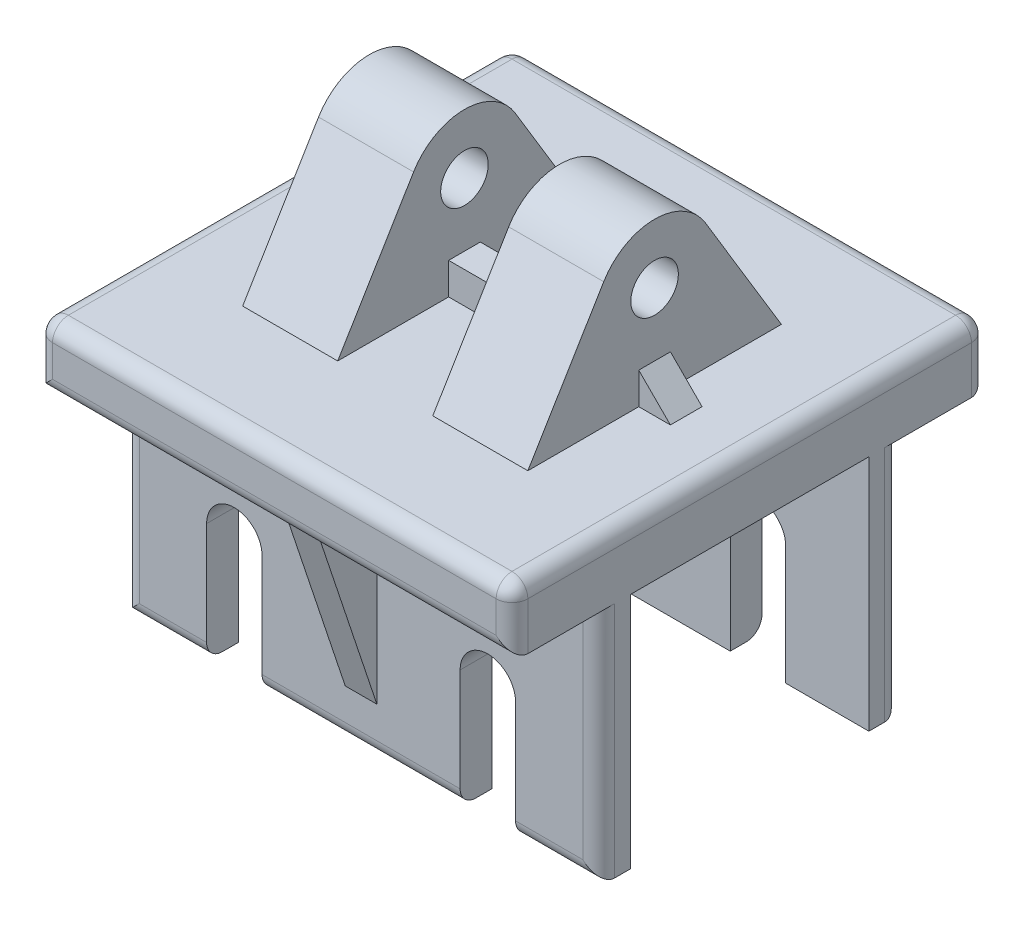
SolidWorks part; units mm, degrees
ref_plane "정면" through (0, 0, 0) normal (0, 0, 1) x (1, 0, 0)
ref_plane "윗면" through (0, 0, 0) normal (0, 1, 0) x (1, 0, 0)
ref_plane "우측면" through (0, 0, 0) normal (1, 0, 0) x (0, 0, -1)
sketch "스케치2" plane through (0, 0, 0) normal (1, 0, 0) x (0, 0, -1)
  line L0 (15.05, 0) -> (-15.05, 0)
  line L1 (-15.05, 0) -> (-15.05, -30)
  line L2 (-15.05, -30) -> (-19.05, -30)
  line L3 (-19.05, -30) -> (-19.05, 0)
  line L5 (19.05, 0) -> (19.05, -30)
  line L6 (19.05, -30) -> (15.05, -30)
  line L7 (15.05, -30) -> (15.05, 0)
  line L8 (-19.05, 0) -> (-30, 0)
  line L9 (-30, 0) -> (-30, 8)
  line L11 (19.05, 0) -> (30, 0)
  line L12 (30, 0) -> (30, 8)
  line L14 (-30, 8) -> (30, 8)
  point P5 (0, 8)
  point P16 (0, 0)
  dimension "D1" = 30.1
  dimension "D2" = 30
  dimension "D3" = 4
  dimension "D4" = 4
  dimension "D5" = 30
  dimension "D6" = 8
  dimension "D7" = 60
extrude "보스-돌출1" add sketch "스케치2" along normal mid plane 60
sketch "스케치3" plane through (0, 0, 0) normal (1, 0, 0) x (0, 0, -1)
  line L0 (-19.05, 0) -> (-27.05, 0)
  line L1 (-30, 0) -> (-19.05, 0) construction
  line L2 (-27.05, 0) -> (-19.05, -24)
  line L3 (-19.05, 0) -> (-19.05, -30) construction
  line L4 (-19.05, -24) -> (-19.05, 0)
  line L5 (19.05, 0) -> (27.05, 0)
  line L6 (19.05, 0) -> (30, 0) construction
  line L7 (27.05, 0) -> (19.05, -24)
  line L8 (19.05, -30) -> (19.05, 0) construction
  line L9 (19.05, -24) -> (19.05, 0)
  dimension "D1" = 8
  dimension "D2" = 24
  dimension "D3" = 24
  dimension "D4" = 8
extrude "보스-돌출2" add sketch "스케치3" along normal mid plane 4
sketch "스케치4" plane through (0, 0, 0) normal (1, 0, 0) x (0, 0, -1)
  line L0 (-6.4216, 23.8746) -> (-16, 8)
  line L1 (30, 8) -> (-30, 8) construction
  line L2 (-16, 8) -> (16, 8)
  line L3 (16, 8) -> (6.4216, 23.8746)
  circle A0 centre (0, 20) radius 3
  arc A1 (6.4216, 23.8746) -> (-6.4216, 23.8746) centre (0, 20) ccw
  point P11 (0, 8)
  dimension "D3" = 6
  dimension "D4" = 15
  dimension "D1" = 32
  dimension "D2" = 12
extrude "보스-돌출3" add sketch "스케치4" along normal mid plane 36
sketch "스케치5" plane through (0, 0, 0) normal (1, 0, 0) x (0, 0, -1)
  line L3 (-6.4216, 23.8746) -> (-16, 8)
  line L4 (-16, 8) -> (16, 8)
  line L5 (16, 8) -> (6.4216, 23.8746)
  line L6 (-6.4216, 23.8746) -> (-16, 8)
  line L7 (-16, 8) -> (16, 8)
  line L8 (16, 8) -> (6.4216, 23.8746)
  arc A1 (6.4216, 23.8746) -> (-6.4216, 23.8746) centre (0, 20) ccw
  arc A2 (6.4216, 23.8746) -> (-6.4216, 23.8746) centre (0, 20) ccw
  dimension "D1" = 0
extrude "컷-돌출1" cut sketch "스케치5" against normal mid plane 12
sketch "스케치6" plane through (0, 0, 0) normal (0, 0, 1) x (1, 0, 0)
  line L0 (-18, 8) -> (-22, 8)
  line L1 (30, 8) -> (-30, 8) construction
  line L2 (-22, 8) -> (-18, 12)
  line L3 (-18, 23.8746) -> (-18, 8) construction
  line L4 (-18, 12) -> (-18, 8)
  line L5 (-6, 8) -> (-6, 12)
  line L6 (-6, 23.8746) -> (-6, 8) construction
  line L7 (-6, 12) -> (6, 12)
  line L8 (6, 23.8746) -> (6, 8) construction
  line L9 (6, 12) -> (6, 8)
  line L10 (18, 8) -> (6, 8) construction
  line L11 (6, 8) -> (-6, 8)
  line L12 (17.9916, 8) -> (18, 12)
  line L13 (18, 23.8746) -> (18, 8) construction
  line L14 (18, 12) -> (21.9916, 8)
  line L15 (21.9916, 8) -> (17.9916, 8)
  dimension "D1" = 4
  dimension "D2" = 4
  dimension "D3" = 4
  dimension "D4" = 4
  dimension "D5" = 4
extrude "보스-돌출4" add sketch "스케치6" along normal mid plane 4
sketch "스케치7" plane through (0, 0, 0) normal (0, 0, 1) x (1, 0, 0)
  line L0 (-19.5, -15) -> (-19.5, -30)
  line L1 (30, -30) -> (-30, -30) construction
  line L2 (-19.5, -30) -> (-12.5, -30)
  line L3 (-12.5, -30) -> (-12.5, -15)
  line L4 (12.5, -15) -> (12.5, -30)
  line L5 (12.5, -30) -> (19.5, -30)
  line L6 (19.5, -30) -> (19.5, -15)
  line L7 (30, 0) -> (-30, 0) construction
  arc A0 (-12.5, -15) -> (-19.5, -15) centre (-16, -15) ccw
  arc A1 (19.5, -15) -> (12.5, -15) centre (16, -15) ccw
  dimension "D1" = 3.5
  dimension "D2" = 3.5
  dimension "D3" = 15
  dimension "D4" = 15
  dimension "D5" = 16
  dimension "D6" = 16
extrude "컷-돌출2" cut sketch "스케치7" against normal mid plane 44
fillet "필렛1" radius 2 20 edges at (0, 0, -30) (30, 4, -30) (0, 8, -30) (-30, 4, -30) (0, 8, 30) (30, 4, 30) (0, 0, 30) (-30, 4, 30) (30, -15, 19.05) (30, -15, -19.05) (-30, -15, -19.05) (-30, -15, 19.05) (24.75, -30, 19.05) (-24.75, -30, 19.05) (0, -30, 19.05) (24.75, -30, -19.05) (-24.75, -30, -19.05) (0, -30, -19.05) (-30, 8, 0) (30, 8, 0)
